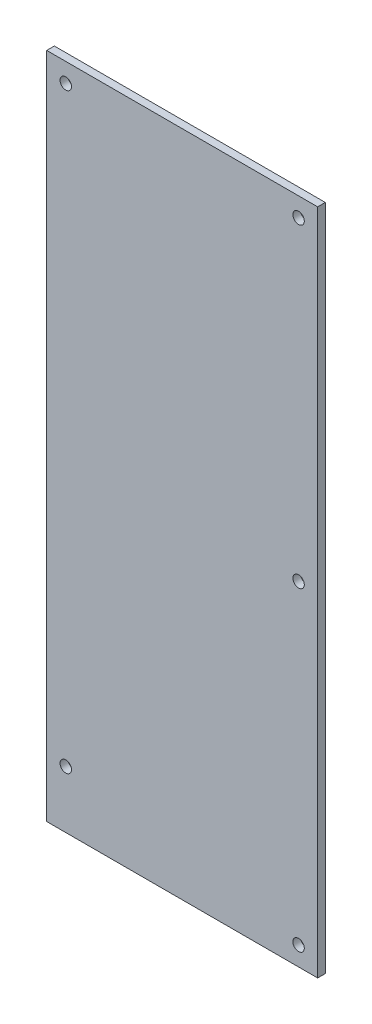
SolidWorks part; units mm, degrees
material "Sklo"
ref_plane "Přední rovina" through (0, 0, 0) normal (0, 0, 1) x (1, 0, 0)
ref_plane "Horní rovina" through (0, 0, 0) normal (0, 1, 0) x (1, 0, 0)
ref_plane "Pravá rovina" through (0, 0, 0) normal (1, 0, 0) x (0, 0, -1)
sketch "Skica1" plane through (0, 0, 0) normal (0, 0, 1) x (1, 0, 0)
  line L1 (71, 175) -> (-71, 175)
  line L2 (71, 175) -> (71, -175)
  line L3 (71, -175) -> (-71, -175)
  line L4 (-71, 175) -> (-71, -175)
  line L5 (71, 175) -> (-71, -175) construction
  line L6 (71, -175) -> (-71, 175) construction
  circle A0 centre (61, 165) radius 3
  circle A1 centre (61, -165) radius 3
  circle A2 centre (61, 0) radius 3
  circle A3 centre (-61, -145) radius 3
  circle A4 centre (-61, 165) radius 3
  point P0 (0, 0)
  dimension "D3" = 6
  dimension "D1" = 142
  dimension "D2" = 350
  dimension "D4" = 10
  dimension "D5" = 10
  dimension "D6" = 10
  dimension "D7" = 10
  dimension "D8" = 10
  dimension "D9" = 10
  dimension "D10" = 10
  dimension "D11" = 10
  dimension "D12" = 30
extrude "Přidat vysunutím1" add sketch "Skica1" along normal blind 4
